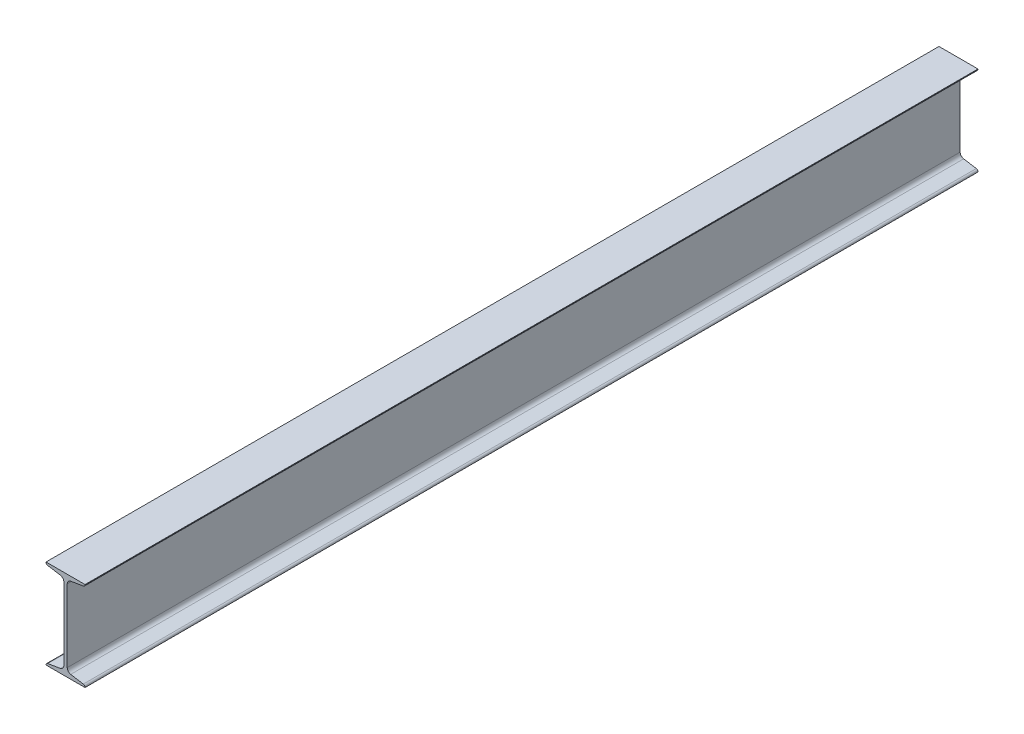
SolidWorks part; units mm, degrees
ref_plane "Front Plane" through (0, 0, 0) normal (0, 0, 1) x (1, 0, 0)
ref_plane "Top Plane" through (0, 0, 0) normal (0, 1, 0) x (1, 0, 0)
ref_plane "Right Plane" through (0, 0, 0) normal (1, 0, 0) x (0, 0, -1)
other "Configuration Table"
sketch "Sketch1" plane through (0, 0, 0) normal (0, 0, 1) x (1, 0, 0)
  line L0 (-66.675, -152.4) -> (-66.675, -152.0363)
  line L1 (-60.7319, -145.0211) -> (-17.7282, -137.8556)
  line L2 (-5.842, -123.825) -> (-5.842, 123.825)
  line L3 (-17.7282, 137.8556) -> (-60.7319, 145.0211)
  line L4 (-66.675, 152.0363) -> (-66.675, 152.4)
  line L5 (-66.675, 152.4) -> (66.675, 152.4)
  line L6 (66.675, 152.4) -> (66.675, 152.0363)
  line L7 (60.7319, 145.0211) -> (17.7282, 137.8556)
  line L8 (5.842, 123.825) -> (5.842, -123.825)
  line L9 (17.7282, -137.8556) -> (60.7319, -145.0211)
  line L10 (66.675, -152.0363) -> (66.675, -152.4)
  line L11 (66.675, -152.4) -> (-66.675, -152.4)
  line L14 (-5.842, 0) -> (5.842, 0) construction
  arc A0 (-17.7282, -137.8556) -> (-5.842, -123.825) centre (-20.066, -123.825) ccw
  arc A1 (-5.842, 123.825) -> (-17.7282, 137.8556) centre (-20.066, 123.825) ccw
  arc A2 (17.7282, 137.8556) -> (5.842, 123.825) centre (20.066, 123.825) ccw
  arc A3 (5.842, -123.825) -> (17.7282, -137.8556) centre (20.066, -123.825) ccw
  arc A4 (60.7319, 145.0211) -> (66.675, 152.0363) centre (59.563, 152.0363) ccw
  arc A5 (-60.7319, 145.0211) -> (-66.675, 152.0363) centre (-59.563, 152.0363) cw
  arc A6 (60.7319, -145.0211) -> (66.675, -152.0363) centre (59.563, -152.0363) cw
  arc A7 (-60.7319, -145.0211) -> (-66.675, -152.0363) centre (-59.563, -152.0363) ccw
  point P30 (0, 152.4)
  point P31 (0, -152.4)
  dimension "D7" = 9.46
  dimension "RI" = 14.224
  dimension "RA" = 7.112
  dimension "BF" = 133.35
  dimension "D6" = 9.46
  dimension "DEPTH" = 304.8
  dimension "TW" = 11.684
  dimension "D1" = 247.65
extrude "Extrude1" add sketch "Sketch1" along normal blind 3050
ref_point "Point1"
ref_point "Point2"
ref_point "Point3"
